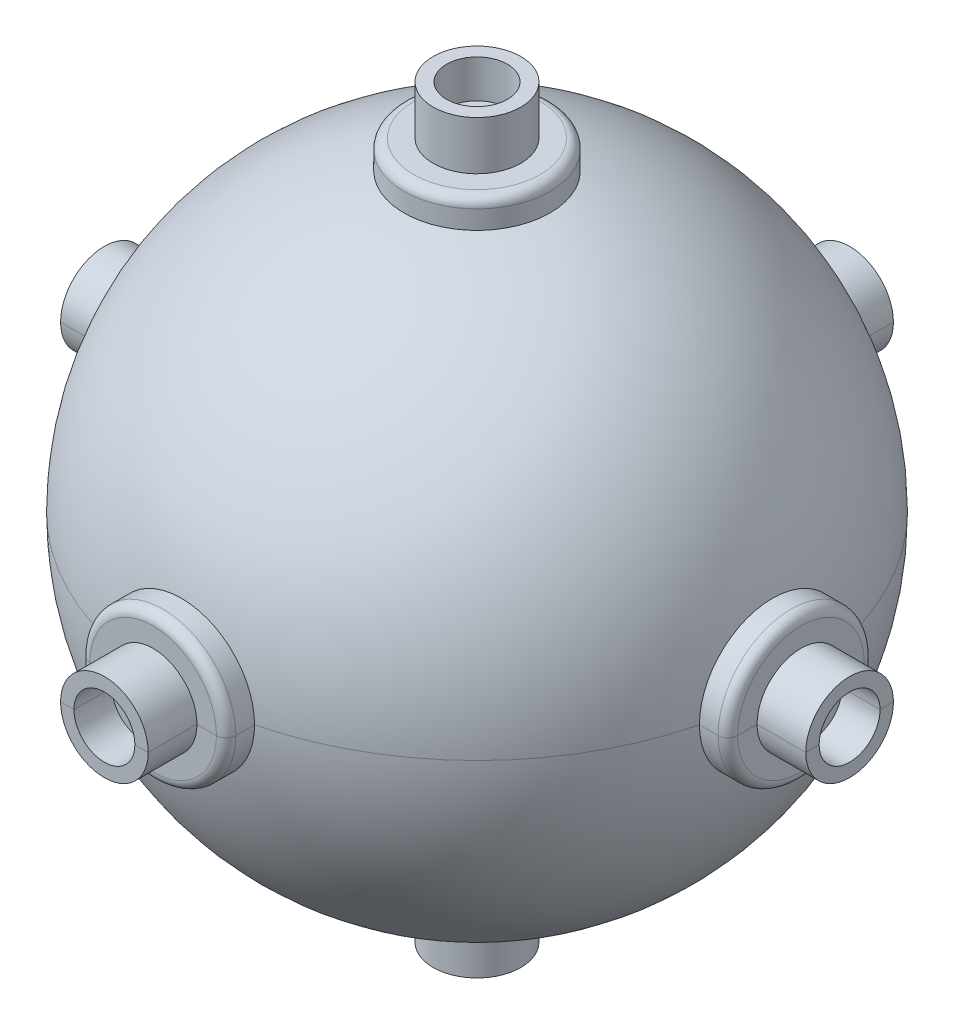
SolidWorks part; units mm, degrees
material "ABS"
ref_plane "Front Plane" through (0, 0, 0) normal (0, 0, 1) x (1, 0, 0)
ref_plane "Top Plane" through (0, 0, 0) normal (0, 1, 0) x (1, 0, 0)
ref_plane "Right Plane" through (0, 0, 0) normal (1, 0, 0) x (0, 0, -1)
sketch "Sketch1" plane through (0, 0, 0) normal (0, 0, 1) x (1, 0, 0)
  line L0 (0, 15.875) -> (0, -15.875)
  arc A0 (0, 15.875) -> (0, -15.875) centre (0, 0) ccw
revolve "Revolve1" add sketch "Sketch1" angle 360 about L0
sketch "Sketch2" plane through (0, 0, 0) normal (0, 0, 1) x (1, 0, 0)
  circle A0 centre (0, 0) radius 15.875 construction
  point P0 (0, 15.875)
  point P1 (0, -15.875)
  point P4 (15.875, 0)
  point P5 (-15.875, 0)
sketch "Sketch5" plane through (0, 0, 0) normal (1, 0, 0) x (0, 0, -1)
  circle A0 centre (0, 0) radius 15.875 construction
  point P0 (-15.875, 0)
  point P1 (15.875, 0)
ref_plane "Plane2" through (0, 0, 15.875) normal (0, 0, 1) x (1, 0, 0)
sketch "Sketch6" plane through (0, 0, 15.875) normal (0, 0, 1) x (1, 0, 0)
  circle A0 centre (0, 0) radius 3.81
extrude "Boss-Extrude1" add sketch "Sketch6" along normal mid plane 2.032 contours A0
sketch "Sketch7" plane through (0, 0, 0) normal (0, 0, 1) x (1, 0, 0)
  line L0 (0, 15.875) -> (0, -15.875) construction
sketch "Sketch9" plane through (0, 0, 16.891) normal (0, 0, 1) x (1, 0, 0)
  circle A0 centre (0, 0) radius 2.286
extrude "Boss-Extrude3" add sketch "Sketch9" along normal blind 2.54
pattern_circular "CirPattern1" count 4 over 360 about axis through (0, 0, 0) along (0, 1, 0) of "Boss-Extrude1", "Boss-Extrude3"
ref_plane "Plane3" through (0, 15.875, 0) normal (0, 1, 0) x (1, 0, 0)
sketch "Sketch10" plane through (0, 15.875, 0) normal (0, 1, 0) x (1, 0, 0)
  circle A0 centre (0, 0) radius 3.81
extrude "Boss-Extrude4" add sketch "Sketch10" along normal mid plane 2.032
sketch "Sketch11" plane through (0, 16.891, 0) normal (0, 1, 0) x (1, 0, 0)
  circle A0 centre (0, 0) radius 2.286
extrude "Boss-Extrude5" add sketch "Sketch11" along normal blind 2.54
mirror "Mirror1" about plane through (0, 0, 0) normal (0, 1, 0) of "Boss-Extrude4", "Boss-Extrude5"
hole_wizard "CBORE for #00 Binding Head Machine Screw1" positions "Sketch12" profile "Sketch13" counterbore size "#00" standard "ANSI Inch"
sketch "Sketch12" plane through (0, 19.431, 0) normal (0, 1, 0) x (1, 0, 0)
  point P0 (0, 0)
sketch "Sketch13" plane through (0, 19.431, 0) normal (1, 0, 0) x (0, 0, 1)
  line L0 (0, 0) -> (0, 4.2297)
  line L1 (0, 4.2297) -> (0.6985, 3.81)
  line L2 (0.6985, 3.81) -> (0.6985, 1.9812)
  line L3 (0.6985, 1.9812) -> (1.5875, 1.9812)
  line L4 (1.5875, 1.9812) -> (1.5875, 0)
  line L5 (1.5875, 0) -> (0, 0)
  line L10 (0, 4.2297) -> (-0.6985, 3.81) construction
  line L11 (0, -6.35) -> (0, 107.95) construction
  dimension "Hole Dia." = 1.397
  dimension "Hole Depth" = 3.81
  dimension "C'Bore Dia." = 3.175
  dimension "C'Bore Depth" = 1.9812
  dimension "Drill Angle" = 118
sketch "Sketch15" plane through (0, 0, 0) normal (0, 1, 0) x (1, 0, 0)
  line L0 (-15.875, 0) -> (15.875, 0) construction
pattern_circular "CirPattern2" count 4 every 90 about axis through (0, 0, 0) along (1, 0, 0) of "CBORE for #00 Binding Head Machine Screw1"
hole_wizard "CBORE for #00 Binding Head Machine Screw3" positions "Sketch18" profile "Sketch19" counterbore size "#00" standard "ANSI Inch"
sketch "Sketch18" plane through (19.431, 0, 0) normal (1, 0, 0) x (0, 0, -1)
  point P0 (0, 0)
sketch "Sketch19" plane through (19.431, 0, 0) normal (0, 1, 0) x (0, 0, -1)
  line L0 (0, 0) -> (0, 4.2297)
  line L1 (0, 4.2297) -> (0.6985, 3.81)
  line L2 (0.6985, 3.81) -> (0.6985, 1.9812)
  line L3 (0.6985, 1.9812) -> (1.5875, 1.9812)
  line L4 (1.5875, 1.9812) -> (1.5875, 0)
  line L5 (1.5875, 0) -> (0, 0)
  line L10 (0, 4.2297) -> (-0.6985, 3.81) construction
  line L11 (0, -6.35) -> (0, 107.95) construction
  dimension "Hole Dia." = 1.397
  dimension "Hole Depth" = 3.81
  dimension "C'Bore Dia." = 3.175
  dimension "C'Bore Depth" = 1.9812
  dimension "Drill Angle" = 118
mirror "Mirror2" about plane through (0, 0, 0) normal (1, 0, 0) of "CBORE for #00 Binding Head Machine Screw3"
fillet "Fillet1" radius 0.508 6 edges at (-3.81, 0, -16.891) (0, -16.891, 3.81) (-16.891, 0, 3.81) (16.891, 0, -3.81) (3.81, 0, 16.891) (0, 16.891, 3.81)
split "Split1" trim tools "Top Plane" bodies to split 113 resulting bodies 114 115
